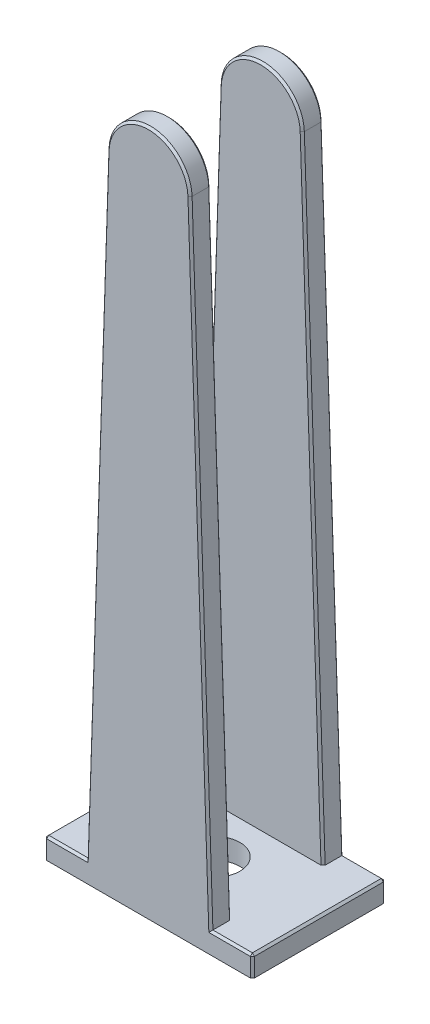
SolidWorks part; units mm, degrees
ref_plane "Front Plane" through (0, 0, 0) normal (0, 0, 1) x (1, 0, 0)
ref_plane "Top Plane" through (0, 0, 0) normal (0, 1, 0) x (1, 0, 0)
ref_plane "Right Plane" through (0, 0, 0) normal (1, 0, 0) x (0, 0, -1)
sketch "Sketch1" plane through (0, 0, 0) normal (0, 0, 1) x (1, 0, 0)
  line L0 (0, 0) -> (-30, 0)
  line L1 (-15, 0) -> (-15, 150) construction
  line L2 (-24.9945, 150.3328) -> (-30, 0)
  line L3 (-5.0055, 150.3328) -> (0, 0)
  arc A0 (-24.9945, 150.3328) -> (-5.0055, 150.3328) centre (-15, 150) cw
  point P7 (-24.7262, 152.3238)
  dimension "D3" = 10
  dimension "D1" = 150
  dimension "D2" = 30
sketch "Sketch2" plane through (0, 0, 0) normal (0, 1, 0) x (1, 0, 0)
  line L0 (0, 0) -> (-40, 0)
  line L1 (0, 0) -> (-30, 0) construction
  line L2 (-40, 0) -> (-40, -16)
  line L3 (-40, -16) -> (0, -16)
  line L5 (0, 0) -> (10, 0)
  line L6 (10, 0) -> (10, -16)
  line L7 (10, -16) -> (0, -16)
  point P5 (0, 0)
  dimension "D1" = 16
  dimension "D2" = 10
  dimension "D3" = 40
extrude "Boss-Extrude2" add sketch "Sketch2" against normal blind 5
extrude "Boss-Extrude3" add sketch "Sketch1" along normal blind 5
mirror "Mirror1" about plane through (10, -5, 16) normal (0, 0, 1) of bodies 103
sketch "Sketch3" plane through (0, -5, 0) normal (0, -1, 0) x (1, 0, 0)
  line L0 (-40, 16) -> (10, 16) construction
  line L1 (-40, 0) -> (-40, 32) construction
  line L2 (10, 32) -> (10, 0) construction
  line L3 (-15, 32) -> (-15, 0) construction
  line L4 (10, 32) -> (-40, 32) construction
  line L5 (10, 0) -> (-40, 0) construction
  circle A0 centre (-15, 16) radius 6
extrude "Cut-Extrude1" cut sketch "Sketch3" against normal through all
chamfer "Chamfer1" distance 0.5 angle 45 22 edges at (-35, 0, 32) (-40, -2.5, 32) (10, -2.5, 32) (-40, 0, 16) (-40, -2.5, 0) (-35, 0, 0) (-27.4972, 75.1664, 5) (-15, 160, 5) (-2.5028, 75.1664, 5) (-27.4972, 75.1664, 27) (-15, 160, 27) (-2.5028, 75.1664, 27) (-27.4972, 75.1664, 0) (-27.4972, 75.1664, 32) (-15, 160, 0) (-15, 160, 32) (10, -2.5, 0) (-2.5028, 75.1664, 0) (5, 0, 0) (10, 0, 16) (5, 0, 32) (-2.5028, 75.1664, 32)
